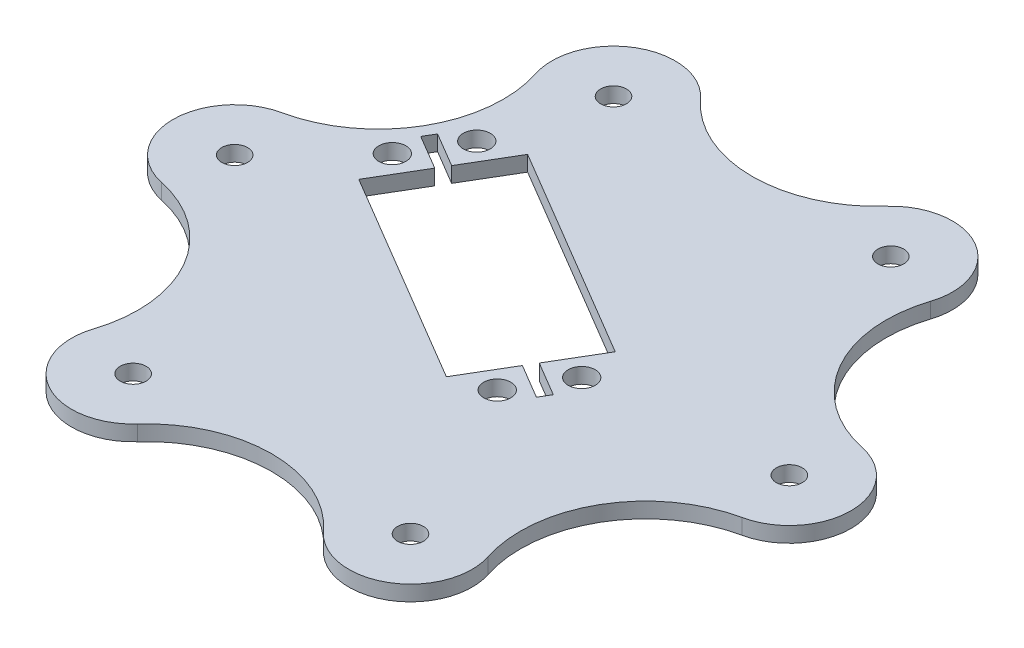
SolidWorks part; units mm, degrees
material "ABS"
ref_plane "前视基准面" through (0, 0, 0) normal (0, 0, 1) x (1, 0, 0)
ref_plane "上视基准面" through (0, 0, 0) normal (0, 1, 0) x (1, 0, 0)
ref_plane "右视基准面" through (0, 0, 0) normal (1, 0, 0) x (0, 0, -1)
other "Configuration Table"
sketch "草图2" plane through (0, 0, 0) normal (0, 1, 0) x (1, 0, 0)
  line L1 (45, 0) -> (22.5, 38.9711)
  line L2 (22.5, 38.9711) -> (-22.5, 38.9711)
  line L3 (-22.5, 38.9711) -> (-45, 0)
  line L4 (-45, 0) -> (-22.5, -38.9711)
  line L5 (-22.5, -38.9711) -> (22.5, -38.9711)
  line L6 (22.5, -38.9711) -> (45, 0)
  circle A0 centre (0, 0) radius 38.9711 construction
  circle A1 centre (-22.5, 38.9711) radius 10
  circle A2 centre (0, 0) radius 6.5
  circle A3 centre (22.5, 38.9711) radius 10
  circle A4 centre (45, 0) radius 10
  circle A5 centre (22.5, -38.9711) radius 10
  circle A6 centre (-22.5, -38.9711) radius 10
  circle A7 centre (-45, 0) radius 10
  circle A8 centre (-51.3411, 29.6418) radius 20.3125
  circle A9 centre (0, 59.2836) radius 20.3125
  circle A10 centre (51.3411, 29.6418) radius 20.3125
  circle A11 centre (51.3411, -29.6418) radius 20.3125
  circle A12 centre (0, -59.2836) radius 20.3125
  circle A13 centre (-51.3411, -29.6418) radius 20.3125
  point P24 (0, 0)
  point P36 (0, 0)
  dimension "D3" = 13
  dimension "D2" = 20
  dimension "D1" = 45
  dimension "D4" = 6
  dimension "D5" = 6
extrude "凸台-拉伸1" add sketch "草图2" along normal blind 2.5
sketch "草图3" plane through (0, 2.5, 0) normal (0, 1, 0) x (1, 0, 0)
  line L7 (-45, 0) -> (-22.5, -38.9711) construction
  line L8 (-22.5, -38.9711) -> (22.5, -38.9711) construction
  line L9 (22.5, -38.9711) -> (45, 0) construction
  line L10 (45, 0) -> (22.5, 38.9711) construction
  line L11 (22.5, 38.9711) -> (-22.5, 38.9711) construction
  line L12 (-22.5, 38.9711) -> (-45, 0) construction
  circle A0 centre (0, 0) radius 38.9711 construction
  circle A7 centre (-22.5, 38.9711) radius 2.1
  circle A8 centre (22.5, 38.9711) radius 2.1
  circle A9 centre (45, 0) radius 2.1
  circle A10 centre (22.5, -38.9711) radius 2.1
  circle A11 centre (-22.5, -38.9711) radius 2.1
  circle A12 centre (-45, 0) radius 2.1
  point P23 (0, 0)
  point P24 (0, 0)
  dimension "D2" = 4.2
  dimension "D1" = 45
  dimension "D3" = 6
extrude "切除-拉伸1" cut sketch "草图3" against normal blind 2.5
sketch "草图4" plane through (0, 2.5, 0) normal (0, 1, 0) x (1, 0, 0)
  line L0 (-21.3209, 23.8559) -> (13.5295, 3.2233)
  line L1 (-21.3209, 23.8559) -> (-31.5098, 6.6459)
  line L2 (-31.5098, 6.6459) -> (3.3405, -13.9867)
  line L3 (3.3405, -13.9867) -> (13.5295, 3.2233)
  line L4 (-26.4154, 15.2509) -> (0, 0) construction
  line L5 (0, 0) -> (53.4973, 0) construction
  dimension "D1" = 30
  dimension "D2" = 40.5
  dimension "D3" = 20
  dimension "D4" = 10
extrude "切除-拉伸2" cut sketch "草图4" against normal blind 10
sketch "草图5" plane through (0, 2.5, 0) normal (0, 1, 0) x (1, 0, 0)
  line L0 (-27.3101, 21.5912) -> (14.4242, -3.117) construction
  line L1 (14.4242, -3.117) -> (9.3298, -11.722) construction
  line L2 (9.3298, -11.722) -> (-32.4046, 12.9862) construction
  line L3 (-32.4046, 12.9862) -> (-27.3101, 21.5912) construction
  line L5 (13.5295, 3.2233) -> (-21.3209, 23.8559) construction
  line L6 (-31.5098, 6.6459) -> (3.3405, -13.9867) construction
  line L7 (-21.3209, 23.8559) -> (-31.5098, 6.6459) construction
  line L8 (3.3405, -13.9867) -> (13.5295, 3.2233) construction
  line L9 (-26.4154, 15.2509) -> (8.435, -5.3817) construction
  line L10 (-14.0847, -3.6704) -> (-3.8957, 13.5396) construction
  circle A0 centre (14.4242, -3.117) radius 2.2
  circle A1 centre (9.3298, -11.722) radius 2.2
  circle A2 centre (-27.3101, 21.5912) radius 2.2
  circle A3 centre (-32.4046, 12.9862) radius 2.2
  dimension "D3" = 4.4
  dimension "D1" = 10
  dimension "D2" = 48.5
extrude "切除-拉伸3" cut sketch "草图5" against normal blind 10
sketch "草图6" plane through (0, 2.5, 0) normal (0, 1, 0) x (1, 0, 0)
  line L1 (-21.3209, 23.8559) -> (-31.5098, 6.6459) construction
  line L2 (-32.5181, 17.7018) -> (-31.4992, 19.4228)
  line L3 (-31.4992, 19.4228) -> (14.5377, -7.8326)
  line L4 (14.5377, -7.8326) -> (13.5188, -9.5536)
  line L6 (-26.4154, 15.2509) -> (8.435, -5.3817) construction
  line L7 (3.3405, -13.9867) -> (13.5295, 3.2233) construction
  line L8 (-32.5181, 17.7018) -> (13.5188, -9.5536)
  dimension "D1" = 2
  dimension "D2" = 6.5
  dimension "D3" = 6.5
extrude "切除-拉伸4" cut sketch "草图6" against normal blind 10
